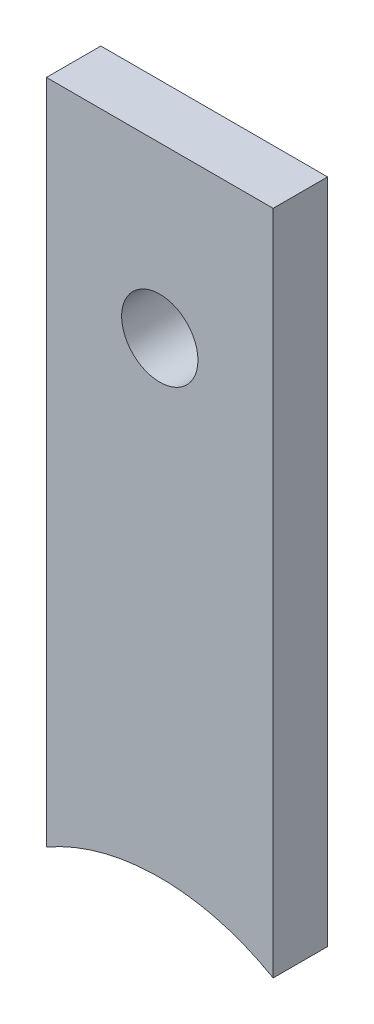
SolidWorks part; units mm, degrees
material "ASTM A36 Steel"
ref_plane "Front Plane" through (0, 0, 0) normal (0, 0, 1) x (1, 0, 0)
ref_plane "Top Plane" through (0, 0, 0) normal (0, 1, 0) x (1, 0, 0)
ref_plane "Right Plane" through (0, 0, 0) normal (1, 0, 0) x (0, 0, -1)
sketch "Sketch1" plane through (0, 0, 0) normal (0, 0, 1) x (1, 0, 0)
  line L2 (-25, -73.5) -> (-25, 73.5)
  line L3 (-25, 73.5) -> (25, 73.5)
  line L4 (25, -73.5) -> (25, 73.5)
  arc A0 (25, -73.5) -> (-25, -73.5) centre (0, -116.8013) ccw
  circle A1 centre (0, 36.1987) radius 8.413
  point P0 (0, 0)
  dimension "D3" = 50
  dimension "D4" = 153
  dimension "D1" = 50
  dimension "D2" = 147
extrude "Boss-Extrude1" add sketch "Sketch1" along normal blind 12
